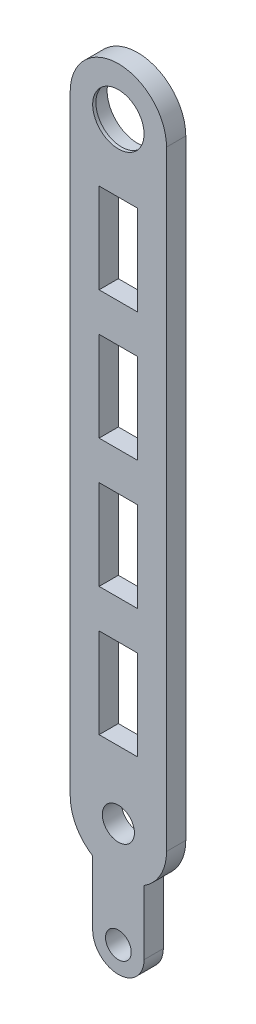
SolidWorks part; units mm, degrees
ref_plane "前视基准面" through (0, 0, 0) normal (0, 0, 1) x (1, 0, 0)
ref_plane "上视基准面" through (0, 0, 0) normal (0, 1, 0) x (1, 0, 0)
ref_plane "右视基准面" through (0, 0, 0) normal (1, 0, 0) x (0, 0, -1)
sketch "草图1" plane through (0, 0, 0) normal (0, 0, 1) x (1, 0, 0)
  line L5 (-8, -127.6886) -> (-8, -107.6886)
  line L16 (-15, -95) -> (-15, 95)
  line L18 (15, -95) -> (15, 95)
  line L19 (-15, -95) -> (15, 95) construction
  line L20 (-15, 95) -> (15, -95) construction
  line L21 (8, -127.6886) -> (8, -107.6886)
  circle A7 centre (0, 95) radius 9.5
  arc A8 (15, 95) -> (-15, 95) centre (0, 95) ccw
  arc A9 (-15, -95) -> (-8, -107.6886) centre (0, -95) ccw
  circle A10 centre (0, -95) radius 5
  circle A11 centre (0, -127.6886) radius 4
  arc A12 (-8, -127.6886) -> (8, -127.6886) centre (0, -127.6886) ccw
  arc A13 (8, -107.6886) -> (15, -95) centre (0, -95) ccw
  point P0 (0, 0)
  dimension "D3" = 16
  dimension "D4" = 19
  dimension "D5" = 8
  dimension "D7" = 30
  dimension "D8" = 95
  dimension "D2" = 10
  dimension "D6" = 15
  dimension "D1" = 190
  dimension "D10" = 20
  dimension "D11" = 95
extrude "凸台-拉伸2" add sketch "草图1" along normal blind 6
sketch "草图2" plane through (0, 0, 6) normal (0, 0, 1) x (1, 0, 0)
  line L0 (0, -1000) -> (0, 49000) construction
  line L2 (-6, 74) -> (6, 74)
  line L3 (-6, 74) -> (-6, 46)
  line L4 (-6, 46) -> (6, 46)
  line L5 (6, 74) -> (6, 46)
  line L6 (-6, 74) -> (6, 46) construction
  line L7 (-6, 46) -> (6, 74) construction
  line L8 (-6, 34) -> (6, 34)
  line L9 (-6, 34) -> (-6, 6)
  line L10 (-6, 6) -> (6, 6)
  line L11 (6, 34) -> (6, 6)
  line L12 (-6, 34) -> (6, 6) construction
  line L13 (-6, 6) -> (6, 34) construction
  line L14 (-6, -6) -> (6, -6)
  line L15 (-6, -6) -> (-6, -34)
  line L16 (-6, -34) -> (6, -34)
  line L17 (6, -6) -> (6, -34)
  line L18 (-6, -6) -> (6, -34) construction
  line L19 (-6, -34) -> (6, -6) construction
  line L20 (-6, -46) -> (6, -46)
  line L21 (-6, -46) -> (-6, -74)
  line L22 (-6, -74) -> (6, -74)
  line L23 (6, -46) -> (6, -74)
  line L24 (-6, -46) -> (6, -74) construction
  line L25 (-6, -74) -> (6, -46) construction
  point P1 (0, 60)
  point P8 (0, 20)
  point P13 (0, -20)
  point P18 (0, -60)
  dimension "D1" = 12
  dimension "D2" = 12
  dimension "D3" = 12
  dimension "D4" = 12
  dimension "D5" = 28
  dimension "D6" = 28
  dimension "D7" = 28
  dimension "D8" = 28
  dimension "D9" = 12
  dimension "D10" = 12
  dimension "D11" = 12
  dimension "D12" = 6
extrude "切除-拉伸1" cut sketch "草图2" against normal blind 6
sketch "草图4" plane through (0, 0, 6) normal (0, 0, 1) x (1, 0, 0)
  circle A0 centre (0, 95) radius 9.5
  circle A1 centre (0, 95) radius 8
  dimension "D1" = 19
  dimension "D2" = 16
extrude "凸台-拉伸4" add sketch "草图4" against normal blind 1
